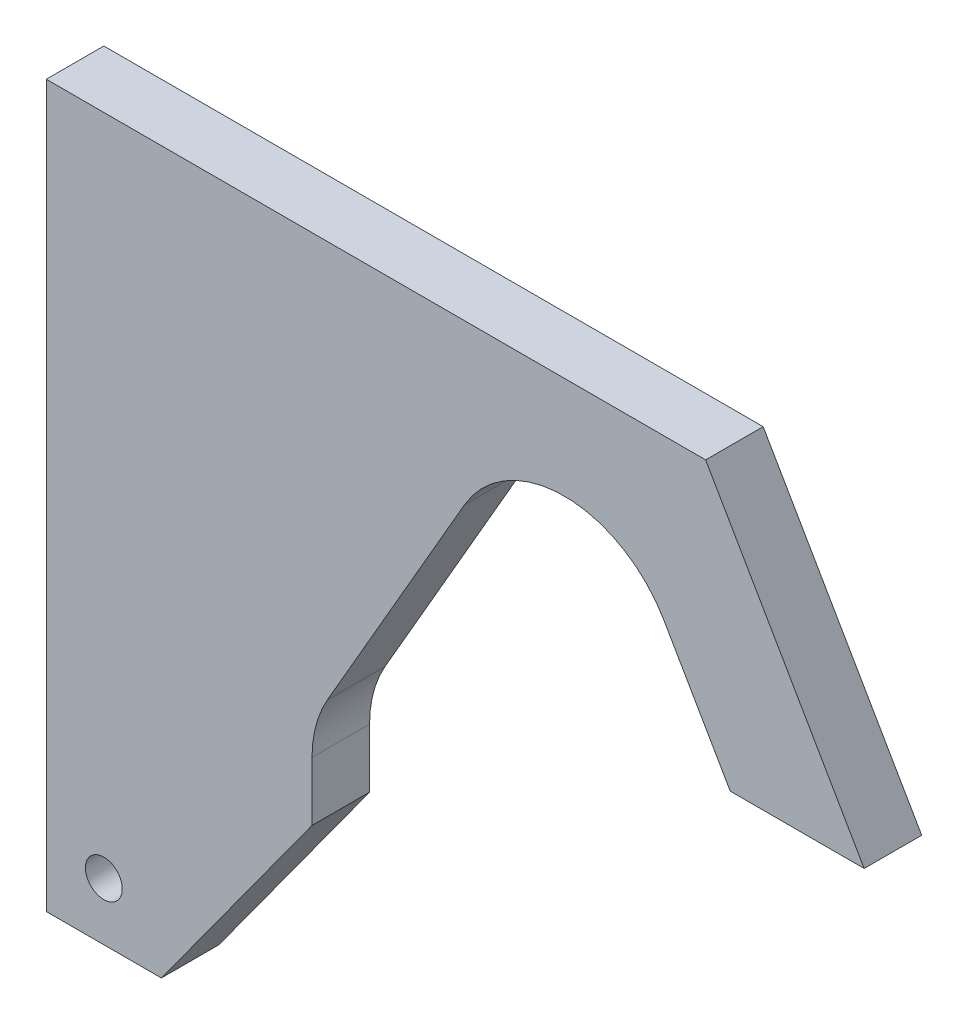
SolidWorks part; units mm, degrees
ref_plane "Front Plane" through (0, 0, 0) normal (0, 0, 1) x (1, 0, 0)
ref_plane "Top Plane" through (0, 0, 0) normal (0, 1, 0) x (1, 0, 0)
ref_plane "Right Plane" through (0, 0, 0) normal (1, 0, 0) x (0, 0, -1)
sketch "Sketch1" plane through (0, 0, 0) normal (0, 0, 1) x (1, 0, 0)
  line L2 (-10.9985, 6.35) -> (-26.1215, -19.8437)
  line L3 (0, 0) -> (0, -20.2229) construction
  line L4 (-57.15, 23.9543) -> (-57.15, -55.5985)
  line L5 (10.9985, 6.35) -> (18.3309, -6.35)
  line L9 (15.6156, 23.9543) -> (-57.15, 23.9543)
  line L10 (-27.823, -26.1937) -> (-27.823, -32.7028)
  line L12 (-27.823, -32.7028) -> (-44.45, -55.5985)
  line L13 (-44.45, -55.5985) -> (-57.15, -55.5985)
  line L14 (15.6156, 23.9543) -> (33.1118, -6.35)
  line L15 (33.1118, -6.35) -> (18.3309, -6.35)
  arc A4 (10.9985, 6.35) -> (-10.9985, 6.35) centre (0, 0) ccw
  arc A11 (-26.1215, -19.8437) -> (-27.823, -26.1937) centre (-15.123, -26.1937) ccw
  point P1 (15.6156, 23.9543)
  dimension "D1" = 25.4
  dimension "D2" = 25.4
  dimension "D3" = 30.2459
  dimension "D4" = 30
  dimension "D6" = 57.15
  dimension "D5" = 30
  dimension "D7" = 12.7
extrude "Boss-Extrude1" add sketch "Sketch1" along normal blind 6.35
sketch "Sketch3" plane through (0, 0, 6.35) normal (0, 0, 1) x (1, 0, 0)
  line L0 (-57.15, 23.9543) -> (-57.15, -55.5985) construction
  line L2 (-57.15, -55.5985) -> (-44.45, -55.5985) construction
  circle A0 centre (-50.8, -49.2485) radius 2.032
  dimension "D1" = 4.064
  dimension "D2" = 6.35
  dimension "D3" = 6.35
extrude "Cut-Extrude1" cut sketch "Sketch3" against normal through all
